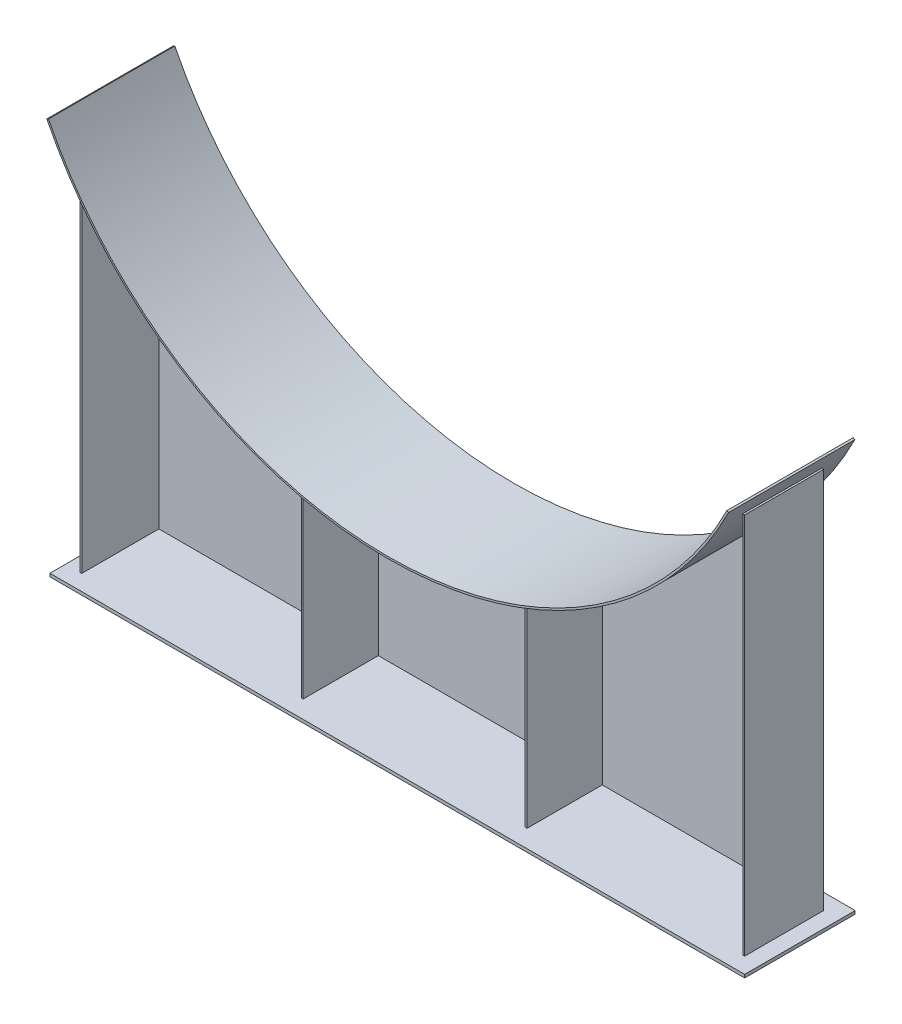
SolidWorks part; units mm, degrees
material "ASTM A36 Steel"
ref_plane "Front Plane" through (0, 0, 0) normal (0, 0, 1) x (1, 0, 0)
ref_plane "Top Plane" through (0, 0, 0) normal (0, 1, 0) x (1, 0, 0)
ref_plane "Right Plane" through (0, 0, 0) normal (1, 0, 0) x (0, 0, -1)
sketch "Sketch2" plane through (0, 0, 0) normal (0, 1, 0) x (1, 0, 0)
  line L22 (0, 0) -> (0, 250)
  line L23 (0, 250) -> (1052.5, 250)
  line L24 (701, 244) -> (701, 6)
  line L25 (6, 0) -> (6, 244)
  line L26 (6, 244) -> (695, 244)
  line L27 (695, 244) -> (695, 6)
  line L28 (695, 6) -> (701, 6)
  line L29 (1052.5, 244) -> (1052.5, 82.9872) construction
  line L30 (1410, 6) -> (1404, 6)
  line L32 (2099, 244) -> (1410, 244)
  line L33 (2099, 0) -> (2099, 244)
  line L35 (2105, 250) -> (1052.5, 250)
  line L36 (2105, 0) -> (2105, 250)
  line L37 (2105, 0) -> (2099, 0)
  line L38 (6, 0) -> (0, 0)
  line L39 (701, 244) -> (1052.5, 244)
  line L40 (6, 244) -> (1052.5, 244) construction
  line L41 (695, 250) -> (695, 6) construction
  line L42 (701, 250) -> (701, 6) construction
  line L43 (1410, 244) -> (1410, 6)
  line L44 (1404, 244) -> (1404, 6)
  line L45 (1404, 244) -> (1052.5, 244)
  point P5 (0, 125)
  point P6 (701, 125)
  dimension "D1" = 250
  dimension "D2" = 1052.5
  dimension "D4" = 6
  dimension "D5" = 6
  dimension "D6" = 238
  dimension "D3" = 701
extrude "Boss-Extrude1" add sketch "Sketch2" along normal blind 1210
ref_plane "Plane1" through (0, 0, -250) normal (0, 0, -1) x (-1, 0, 0)
sketch "Sketch3" plane through (0, 0, -250) normal (0, 0, -1) x (-1, 0, 0)
  line L0 (-1052.5, 0) -> (-1052.5, 600) construction
  line L1 (-2105, 0) -> (0, 0) construction
  line L2 (-2105, 1210) -> (0, 1210)
  arc A0 (-2099, 1210) -> (0, 1210) centre (-1049.5, 1807.8207) ccw
  dimension "D1" = 600
extrude "Cut-Extrude1" cut sketch "Sketch3" against normal through all contours L2 A0
sketch "Sketch4" plane through (0, 0, 0) normal (0, 1, 0) x (1, 0, 0)
  line L0 (2105, 250) -> (0, 250) construction
  line L5 (2155, 125) -> (-45, 125) construction
  line L6 (2155, 300) -> (-45, 300)
  line L8 (2155, 300) -> (2155, -50)
  line L9 (2155, -50) -> (-45, -50)
  line L10 (-45, 300) -> (-45, -50)
  point P0 (1052.5, 250)
  dimension "D1" = 2200
  dimension "D2" = 350
  dimension "D3" = 50
  dimension "D4" = 50
extrude "Boss-Extrude2" add sketch "Sketch4" against normal blind 10
sketch "Sketch10" plane through (0, 0, -250) normal (0, 0, -1) x (-1, 0, 0)
  line L0 (29.8665, 1265.7803) -> (24.5046, 1268.4729)
  line L1 (-2123.5712, 1268.6055) -> (-2128.9334, 1265.9135)
  arc A1 (-2128.9334, 1265.9135) -> (29.8665, 1265.7803) centre (-1049.5, 1807.8207) ccw
  arc A2 (-2093.7865, 1212.9697) -> (-5.2135, 1212.9697) centre (-1049.5, 1807.8207) ccw
  arc A3 (-2123.5712, 1268.6055) -> (24.5046, 1268.4729) centre (-1049.5, 1807.8207) ccw
  dimension "D3" = 63.4
  dimension "D4" = 63.4
  dimension "D1" = 6
  dimension "D2" = 6
extrude "Boss-Extrude14" add sketch "Sketch10" against normal blind 400 from offset 75 separate body
